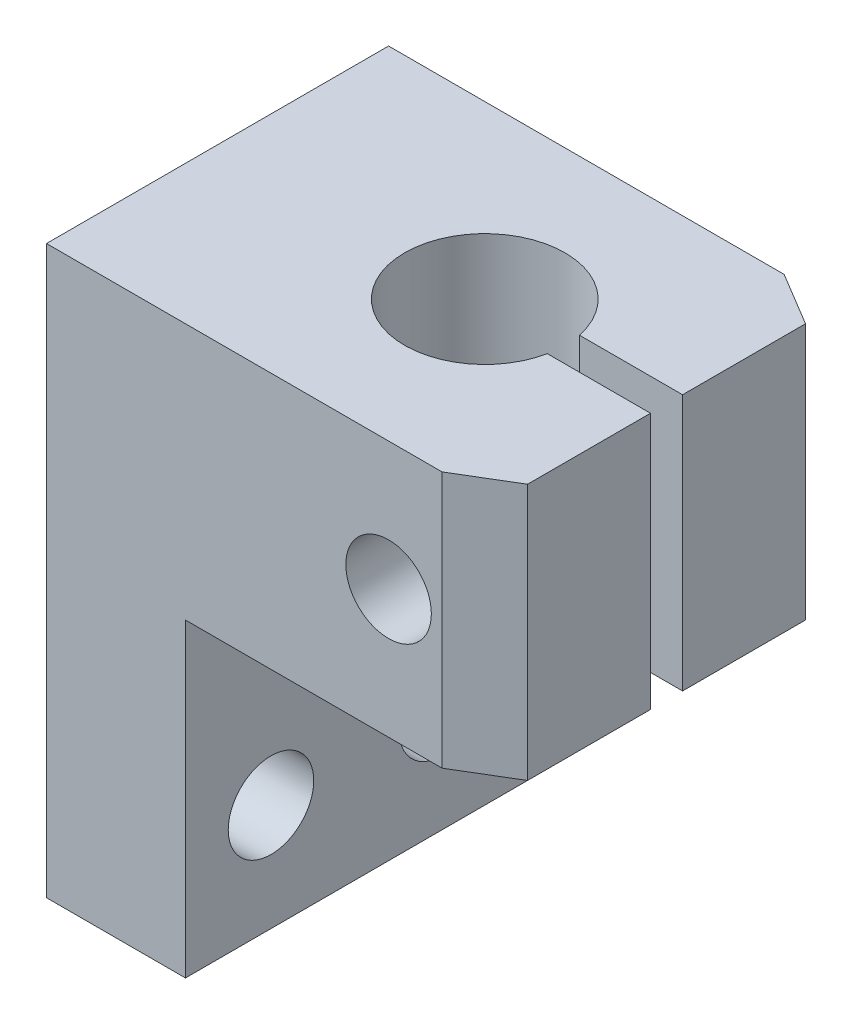
SolidWorks part; units mm, degrees
ref_plane "Front Plane" through (0, 0, 0) normal (0, 0, 1) x (1, 0, 0)
ref_plane "Top Plane" through (0, 0, 0) normal (0, 1, 0) x (1, 0, 0)
ref_plane "Right Plane" through (0, 0, 0) normal (1, 0, 0) x (0, 0, -1)
sketch "Sketch1" plane through (0, 0, 0) normal (0, 0, 1) x (1, 0, 0)
  line L2 (0, 0) -> (0, -53)
  line L3 (0, -53) -> (13, -53)
  line L4 (13, -24) -> (13, -53)
  line L5 (0, 0) -> (42, 0)
  line L6 (0, 0) -> (0, -20.3398)
  line L7 (13, -24) -> (42, -24)
  line L8 (42, 0) -> (42, -24)
  circle A0 centre (32, -12) radius 4
  point P11 (42, -12)
  dimension "D6" = 8
  dimension "D1" = 53
  dimension "D2" = 42
  dimension "D3" = 13
  dimension "D4" = 29
  dimension "D5" = 32
extrude "Boss-Extrude1" add sketch "Sketch1" along normal blind 32 contours L8 L5 L2 L3 L4 L7 A0
sketch "Sketch2" plane through (0, 0, 0) normal (-1, 0, 0) x (0, 0, 1)
  line L0 (8, -43) -> (24, -43) construction
  line L1 (32, -53) -> (0, -53) construction
  circle A0 centre (8, -43) radius 4
  circle A1 centre (24, -43) radius 4
  point P6 (16, -53)
  point P7 (16, -43)
  dimension "D1" = 8
  dimension "D2" = 16
  dimension "D3" = 10
extrude "Cut-Extrude1" cut sketch "Sketch2" against normal through all
sketch "Sketch3" plane through (0, -24, 0) normal (0, -1, 0) x (1, 0, 0)
  line L0 (42, 32) -> (42, 0) construction
  line L2 (32.3485, 17.5) -> (42, 17.5)
  line L4 (32.3485, 14.5) -> (42, 14.5)
  line L5 (42, 17.5) -> (42, 14.5)
  arc A0 (32.3485, 17.5) -> (32.3485, 14.5) centre (25, 16) ccw
  point P4 (42, 16)
  point P9 (42, 16)
  dimension "D2" = 15
  dimension "D1" = 17
  dimension "D3" = 3
extrude "Cut-Extrude2" cut sketch "Sketch3" against normal through all
chamfer "Chamfer1" distance 5 distance2 3 1 edges at (42, -12, 32)
chamfer "Chamfer2" distance 3 distance2 5 1 edges at (42, -12, 0)
